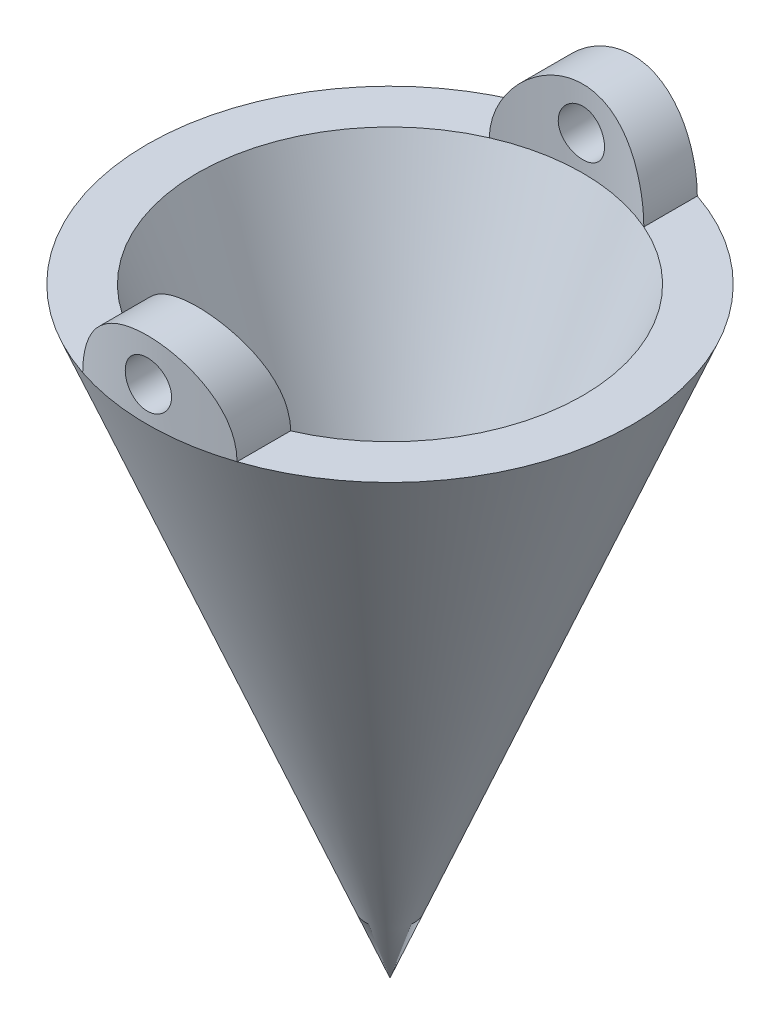
SolidWorks part; units mm, degrees
ref_plane "Alzado" through (0, 0, 0) normal (0, 0, 1) x (1, 0, 0)
ref_plane "Planta" through (0, 0, 0) normal (0, 1, 0) x (1, 0, 0)
ref_plane "Vista lateral" through (0, 0, 0) normal (1, 0, 0) x (0, 0, -1)
sketch "Croquis1" plane through (0, 0, 0) normal (0, 0, 1) x (1, 0, 0)
  line L0 (0, 0) -> (-31.4487, 77.8383)
  line L1 (-31.4487, 77.8383) -> (-24.9775, 77.8383)
  line L2 (-24.9775, 77.8383) -> (0, 16.0168)
  line L4 (0, 0) -> (0, 16.0168)
  ellipse E0 centre (0, 47.8383) end of major axis (0, 67.8383) minor radius 10 construction
  point P6 (0, 0)
  point P12 (0, 0)
  point P13 (0, 0)
  point P14 (0, 0)
  dimension "D1" = 40
  dimension "D2" = 20
  dimension "D3" = 6
  dimension "D4" = 10
  dimension "D5" = 22
revolve "Revolución1" add sketch "Croquis1" angle 360 about L4
sketch "Croquis2" plane through (0, 77.8383, 0) normal (0, 1, 0) x (1, 0, 0)
  line L0 (10, -22.8883) -> (10, -29.8165)
  line L1 (-10, -22.8883) -> (-10, -29.8165)
  line L2 (0, 0) -> (31.4487, 0) construction
  line L3 (10, 22.8883) -> (10, 29.8165)
  line L4 (-10, 22.8883) -> (-10, 29.8165)
  arc A0 (-10, -22.8883) -> (10, -22.8883) centre (0, 0) ccw
  circle A1 centre (0, 0) radius 24.9775 construction
  arc A2 (-10, -29.8165) -> (10, -29.8165) centre (0, 0) ccw
  circle A4 centre (0, 0) radius 31.4487 construction
  arc A5 (-10, 22.8883) -> (10, 22.8883) centre (0, 0) cw
  arc A6 (-10, 29.8165) -> (10, 29.8165) centre (0, 0) cw
  point P9 (0, -24.9775)
  point P12 (0, -31.4487)
  dimension "D1" = 20
extrude "Saliente-Extruir1" add sketch "Croquis2" along normal blind 10
ref_plane "Plano1" through (0, 0, 32) normal (0, 0, 1) x (1, 0, 0)
sketch "Croquis3" plane through (0, 0, 32) normal (0, 0, 1) x (1, 0, 0)
  line L7 (10, 87.8383) -> (10, 77.8383)
  line L8 (0, 87.8383) -> (10, 87.8383)
  line L9 (0, 77.8383) -> (0, 87.8383) construction
  arc A2 (0, 87.8383) -> (10, 77.8383) centre (0, 77.8383) cw
extrude "Cortar-Extruir1" cut sketch "Croquis3" against normal through all
sketch "Croquis5" plane through (0, 0, 32) normal (0, 0, 1) x (1, 0, 0)
  line L0 (-10, 77.8383) -> (-10, 87.8383)
  line L1 (-10, 87.8383) -> (0, 87.8383)
  line L2 (0, 87.8383) -> (-10, 87.8383) construction
  line L3 (10, 77.8383) -> (-10, 77.8383) construction
  circle A0 centre (0, 82.3383) radius 3
  arc A1 (0, 87.8383) -> (-10, 77.8383) centre (0, 77.8383) ccw
  point P12 (0, 77.8383)
  point P13 (0, 0)
  point P14 (0, 82.3443)
  dimension "D1" = 6
  dimension "D2" = 4.5
extrude "Cortar-Extruir2" cut sketch "Croquis5" against normal through all
